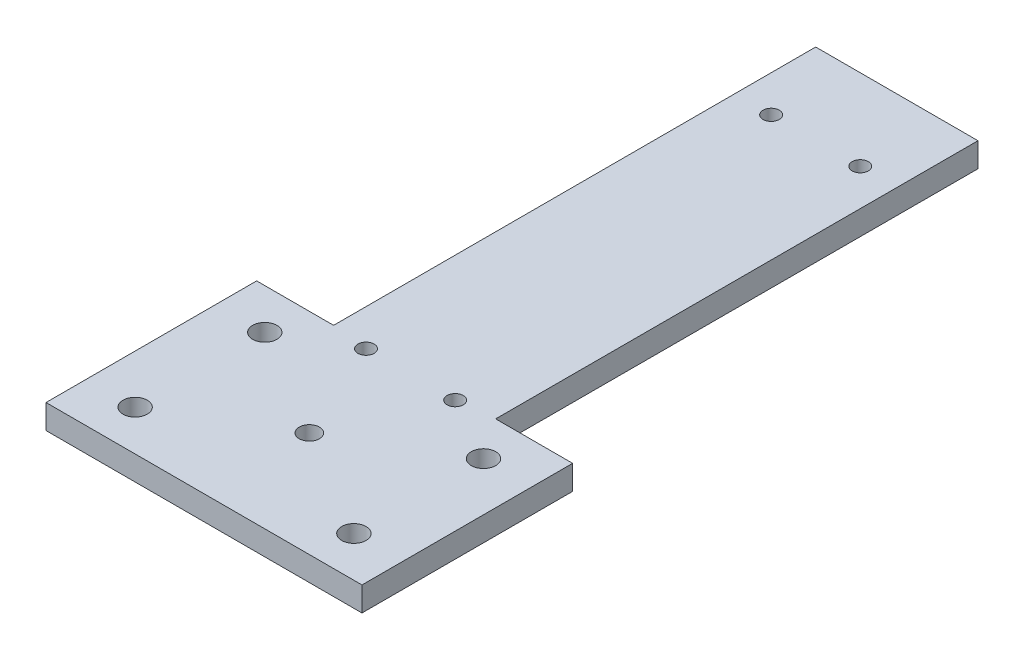
SolidWorks part; units mm, degrees
ref_plane "Front Plane" through (0, 0, 0) normal (1, 0, 0) x (0, 1, 0)
ref_plane "Top Plane" through (0, 0, 0) normal (0, 0, 1) x (0, 1, 0)
ref_plane "Right Plane" through (0, 0, 0) normal (0, 1, 0) x (-1, 0, 0)
sketch "Sketch2" plane through (0, 1180.4362, 0) normal (0, 1, 0) x (1, 0, 0)
  line L0 (845.275, -1925.9111) -> (831.275, -1925.9111) construction
  line L8 (791.275, -1925.9111) -> (777.275, -1925.9111) construction
  line L16 (845.275, -1925.9111) -> (831.275, -1925.9111)
  line L24 (791.275, -1925.9111) -> (777.275, -1925.9111)
  line L32 (791.275, -1801.9111) -> (791.275, -1920.9111)
  line L33 (772.275, -1920.9111) -> (791.275, -1920.9111)
  line L34 (772.275, -1920.9111) -> (772.275, -1972.9111)
  line L35 (772.275, -1972.9111) -> (850.275, -1972.9111)
  line L36 (850.275, -1920.911) -> (850.275, -1972.9111)
  line L37 (831.275, -1920.911) -> (831.3406, -1801.9111)
  line L38 (791.275, -1801.9111) -> (831.3406, -1801.9111)
  line L39 (831.275, -1920.911) -> (850.275, -1920.911)
  line L40 (796.275, -1936.9111) -> (796.275, -1806.9111) construction
  line L41 (815.275, -1806.9111) -> (826.275, -1806.9111) construction
  line L43 (777.275, -1967.9111) -> (777.275, -1925.9111) construction
  line L44 (845.275, -1967.9111) -> (831.275, -1967.9111) construction
  line L45 (845.275, -1925.9111) -> (845.275, -1967.9111) construction
  circle A0 centre (811.275, -1946.9111) radius 2.5
  circle A1 centre (784.275, -1930.9111) radius 3
  circle A2 centre (784.275, -1930.9111) radius 3
  circle A3 centre (784.275, -1962.9111) radius 3
  circle A4 centre (784.275, -1962.9111) radius 3
  circle A5 centre (838.275, -1930.9111) radius 3
  circle A6 centre (838.275, -1930.9111) radius 3
  circle A7 centre (838.275, -1962.9111) radius 3
  circle A8 centre (838.275, -1962.9111) radius 3
  circle A9 centre (800.275, -1921.9111) radius 2
  circle A10 centre (800.275, -1921.9111) radius 2
  circle A11 centre (800.275, -1821.9111) radius 2
  circle A12 centre (800.275, -1821.9111) radius 2
  circle A13 centre (822.275, -1921.9111) radius 2
  circle A14 centre (822.275, -1921.9111) radius 2
  circle A15 centre (822.275, -1821.9111) radius 2
  circle A16 centre (822.275, -1821.9111) radius 2
  dimension "D16" = 5
  dimension "D9" = 5
  dimension "D10" = 5
  dimension "D11" = 5
  dimension "D12" = 5
  dimension "D13" = 5
  dimension "D14" = 40
  dimension "D15" = 5
  dimension "D17" = 39
  dimension "D18" = 26
  dimension "D1" = 0
  dimension "D2" = 0
  dimension "D3" = 0
  dimension "D4" = 0
  dimension "D5" = 0
  dimension "D6" = 0
  dimension "D7" = 0
  dimension "D8" = 0
extrude "Boss-Extrude1" add sketch "Sketch2" along normal blind 6
